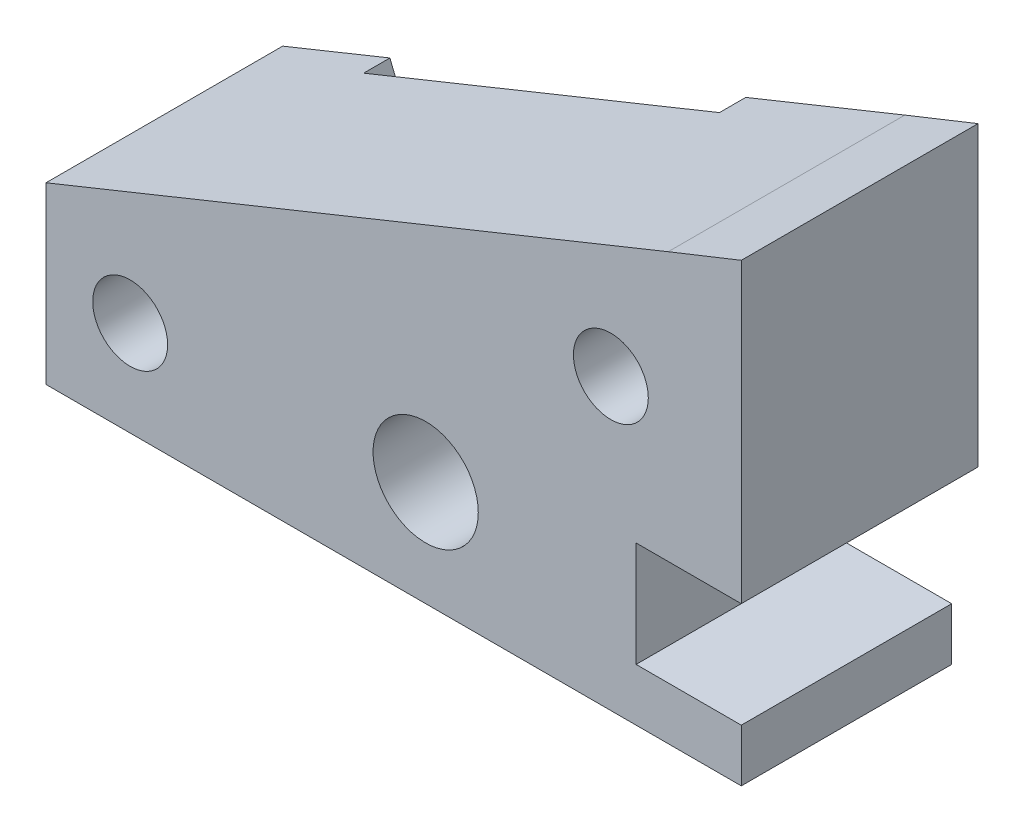
SolidWorks part; units mm, degrees
material "2024 Alloy"
ref_plane "Front Plane" through (0, 0, 0) normal (0, 0, 1) x (1, 0, 0)
ref_plane "Top Plane" through (0, 0, 0) normal (0, 1, 0) x (1, 0, 0)
ref_plane "Right Plane" through (0, 0, 0) normal (1, 0, 0) x (0, 0, -1)
sketch "Sketch1" plane through (0, 0, 0) normal (0, 0, 1) x (1, 0, 0)
  line L0 (6.35, 1.5875) -> (9.525, 1.5875)
  line L1 (9.525, 1.5875) -> (9.525, 4.2246)
  line L2 (6.35, -1.5875) -> (9.525, -1.5875)
  line L3 (9.525, -1.5875) -> (9.525, -3.175)
  line L4 (9.525, -3.175) -> (-11.4587, -3.175)
  line L5 (0, 0) -> (-23.8132, 0) construction
  line L6 (-8.224, 3.404) -> (-3.6768, -7.8507) construction
  line L7 (2.515, 7.7428) -> (9.4959, -9.5353) construction
  line L9 (-2.3364, 5.7828) -> (1.0962, -2.7131) construction
  line L10 (9.525, 4.2246) -> (9.525, 10.5626)
  line L11 (9.525, 10.5626) -> (7.3193, 9.6839)
  line L13 (0, 0) -> (12.2478, 0) construction
  line L18 (-11.4587, 2.0971) -> (7.3193, 9.6839)
  line L22 (6.35, -1.5875) -> (6.35, 1.5875)
  line L24 (-11.4587, -3.175) -> (-11.4587, 2.0971)
  circle A0 centre (0, 0) radius 1.5875
  circle A1 centre (-8.9187, -0.301) radius 1.1303
  circle A2 centre (5.5884, 5.5602) radius 1.1303
extrude "Boss-Extrude1" add sketch "Sketch1" along normal blind 7.1437
sketch "Sketch2" plane through (0, 0, 0) normal (0, 0, 1) x (1, 0, 0)
  line L0 (6.35, 1.5875) -> (9.525, 1.5875) construction
  line L1 (9.525, 1.5875) -> (6.1484, 1.5875)
  line L2 (-11.4587, -3.175) -> (9.525, -3.175) construction
  line L4 (9.525, 1.5875) -> (9.525, 10.5626) construction
  line L6 (-8.224, 3.404) -> (-4.8525, -4.9408) construction
  line L7 (7.3193, 9.6839) -> (-11.4587, 2.0971) construction
  line L8 (2.515, 7.7428) -> (3.5036, 5.296) construction
  line L9 (-8.224, 3.404) -> (-5.5659, -3.175)
  line L10 (-8.224, 3.404) -> (2.515, 7.7428)
  line L11 (2.515, 7.7428) -> (3.5036, 5.296)
  line L13 (9.525, 1.5875) -> (9.525, -3.175)
  line L14 (9.525, -3.175) -> (-5.5659, -3.175)
  circle A0 centre (-8.9187, -0.301) radius 1.1303 construction
  circle A1 centre (5.5884, 5.5602) radius 1.1303 construction
  circle A2 centre (0, 0) radius 1.5875
  arc A4 (6.1484, 1.5875) -> (3.5036, 5.296) centre (0, 0) ccw
extrude "Cut-Extrude1" cut sketch "Sketch2" along normal blind 0.7937
